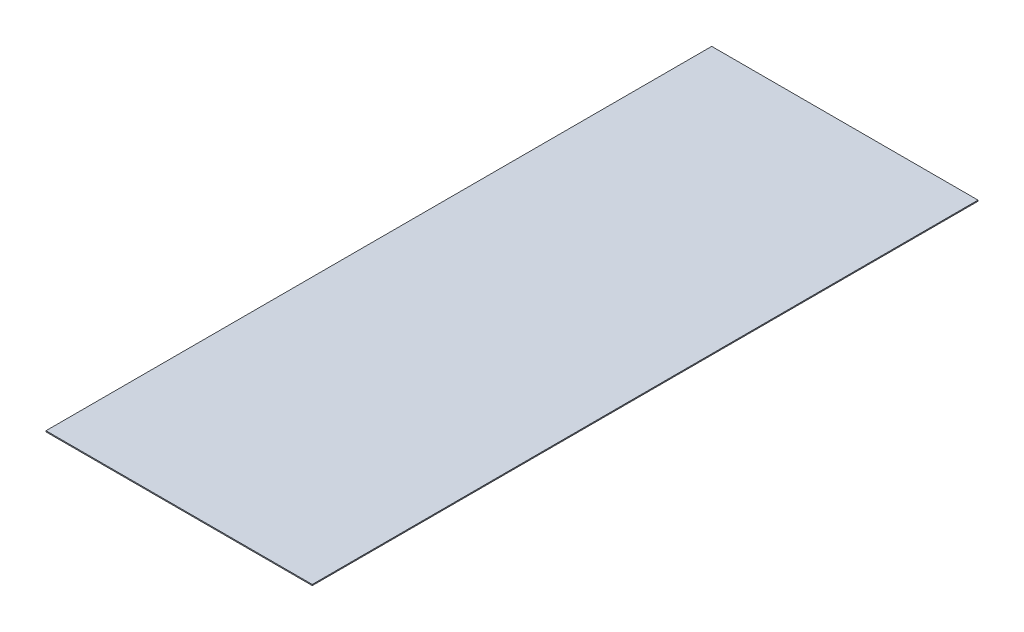
SolidWorks part; units mm, degrees
material "ASTM A36 Acero"
ref_plane "Alzado" through (0, 0, 0) normal (0, 0, 1) x (1, 0, 0)
ref_plane "Planta" through (0, 0, 0) normal (0, 1, 0) x (1, 0, 0)
ref_plane "Vista lateral" through (0, 0, 0) normal (1, 0, 0) x (0, 0, -1)
sketch "Croquis1" plane through (0, 0, 0) normal (0, 1, 0) x (1, 0, 0)
  line L1 (-609.6, -1524) -> (609.6, -1524)
  line L2 (-609.6, -1524) -> (-609.6, 1524)
  line L3 (-609.6, 1524) -> (609.6, 1524)
  line L4 (609.6, -1524) -> (609.6, 1524)
  line L5 (-609.6, -1524) -> (609.6, 1524) construction
  line L6 (-609.6, 1524) -> (609.6, -1524) construction
  point P0 (0, 0)
  dimension "D1" = 3048
  dimension "D2" = 1219.2
extrude "Saliente-Extruir1" add sketch "Croquis1" along normal blind 4.8
